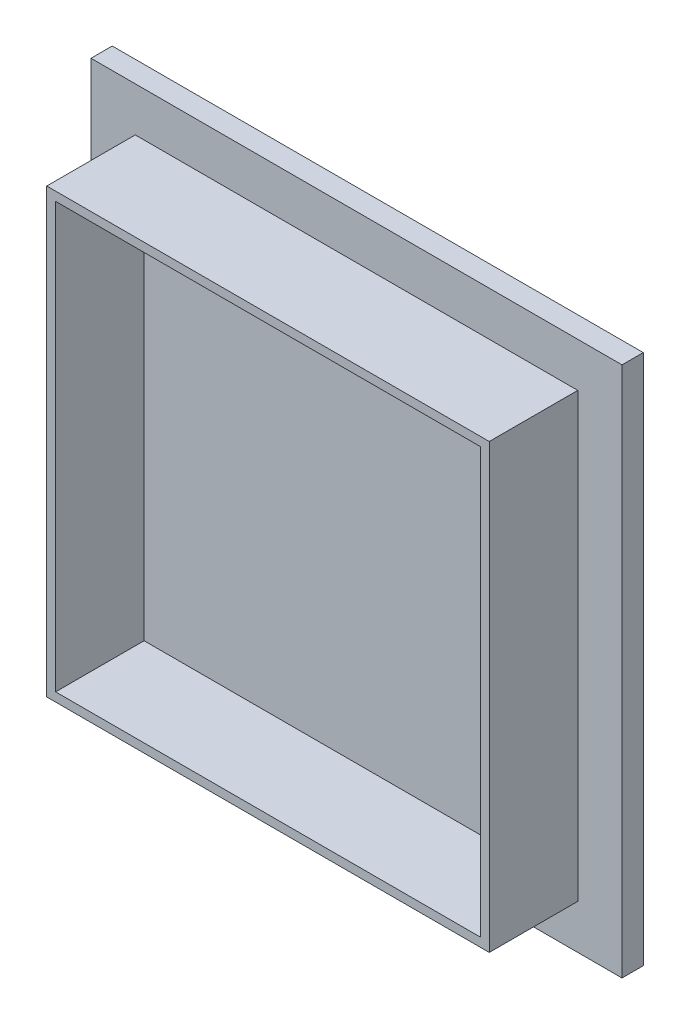
SolidWorks part; units mm, degrees
ref_plane "Plan de face" through (0, 0, 0) normal (0, 0, 1) x (1, 0, 0)
ref_plane "Plan de dessus" through (0, 0, 0) normal (0, 1, 0) x (1, 0, 0)
ref_plane "Plan de droite" through (0, 0, 0) normal (1, 0, 0) x (0, 0, -1)
sketch "Esquisse1" plane through (0, 0, 0) normal (0, 0, 1) x (1, 0, 0)
  line L1 (-150, 150) -> (150, 150)
  line L2 (-150, 150) -> (-150, -150)
  line L3 (-150, -150) -> (150, -150)
  line L4 (150, 150) -> (150, -150)
  line L5 (-150, 150) -> (150, -150) construction
  line L6 (-150, -150) -> (150, 150) construction
  point P0 (0, 0)
  dimension "D1" = 300
  dimension "D2" = 300
extrude "Boss.-Extru.1" add sketch "Esquisse1" along normal blind 12
sketch "Esquisse2" plane through (0, 0, 12) normal (0, 0, 1) x (1, 0, 0)
  line L1 (-125, 125) -> (125, 125)
  line L2 (-125, 125) -> (-125, -125)
  line L3 (-125, -125) -> (125, -125)
  line L4 (125, 125) -> (125, -125)
  line L5 (-125, 125) -> (125, -125) construction
  line L6 (-125, -125) -> (125, 125) construction
  point P0 (0, 0)
  dimension "D1" = 250
  dimension "D2" = 250
extrude "Boss.-Extru.2" add sketch "Esquisse2" along normal blind 50
sketch "Esquisse3" plane through (0, 0, 0) normal (0, 0, -1) x (-1, 0, 0)
  line L0 (0, 24.5624) -> (0, -30.7642) construction
  line L1 (-23.8509, 80) -> (24.5969, 80) construction
  line L2 (-150, 150) -> (150, 150) construction
  line L3 (-15, 80) -> (15, 80) construction
  line L4 (-15, 92.5) -> (15, 92.5)
  line L5 (-15, 67.5) -> (15, 67.5)
  arc A0 (-15, 92.5) -> (-15, 67.5) centre (-15, 80) ccw
  arc A1 (15, 67.5) -> (15, 92.5) centre (15, 80) ccw
  point P9 (0, 80)
  point P14 (-15, 125)
  dimension "D1" = 70
extrude "Enlèv. mat.-Extru.1" cut sketch "Esquisse3" against normal blind 10
sketch "Esquisse4" plane through (0, 0, 0) normal (0, 0, -1) x (-1, 0, 0)
  line L1 (-27.911, 135.9762) -> (27.089, 135.9762)
  line L2 (-27.911, 135.9762) -> (-27.911, 92.5)
  line L3 (-27.911, 92.5) -> (27.089, 92.5)
  line L4 (27.089, 135.9762) -> (27.089, 92.5)
  line L5 (-27.911, 135.9762) -> (27.089, 92.5) construction
  line L6 (-27.911, 92.5) -> (27.089, 135.9762) construction
  line L8 (15, 92.5) -> (-15, 92.5) construction
  point P0 (-0.411, 114.2381)
  dimension "D1" = 55
extrude "Enlèv. mat.-Extru.2" cut sketch "Esquisse4" against normal blind 5 from offset 5 offset against normal yes
sketch "Esquisse6" plane through (0, 0, 62) normal (0, 0, 1) x (1, 0, 0)
  line L1 (-120, 120) -> (120, 120)
  line L2 (-120, 120) -> (-120, -120)
  line L3 (-120, -120) -> (120, -120)
  line L4 (120, 120) -> (120, -120)
  line L5 (-120, 120) -> (120, -120) construction
  line L6 (-120, -120) -> (120, 120) construction
  point P0 (0, 0)
  dimension "D1" = 240
  dimension "D2" = 240
extrude "Enlèv. mat.-Extru.3" cut sketch "Esquisse6" against normal blind 50
